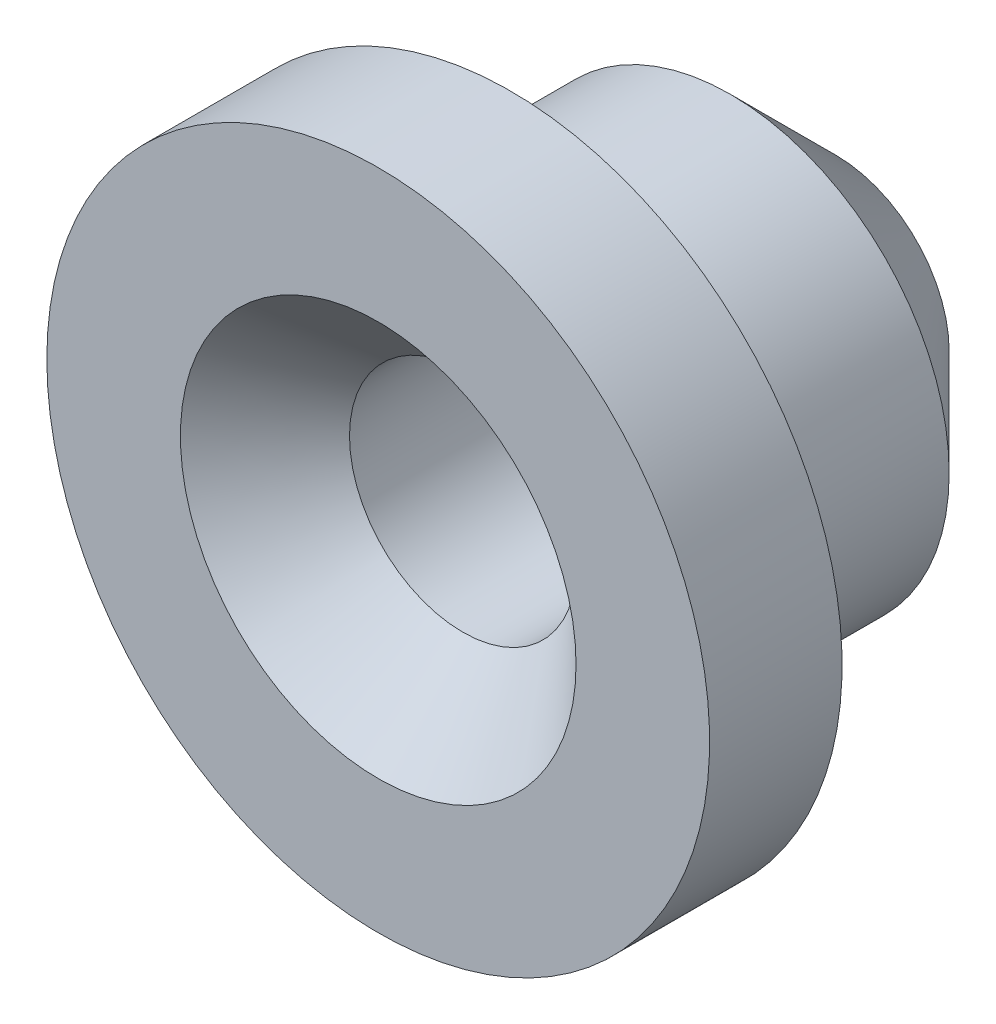
SolidWorks part; units mm, degrees
ref_plane "Front Plane" through (0, 0, 0) normal (0, 0, 1) x (1, 0, 0)
ref_plane "Top Plane" through (0, 0, 0) normal (0, 1, 0) x (1, 0, 0)
ref_plane "Right Plane" through (0, 0, 0) normal (1, 0, 0) x (0, 0, -1)
sketch "Sketch1" plane through (0, 0, 0) normal (0, 0, 1) x (1, 0, 0)
  circle A0 centre (-11.194, 3.0859) radius 4.9276
  dimension "D1" = 9.8552
extrude "Boss-Extrude1" add sketch "Sketch1" along normal blind 7.9375
sketch "Sketch4" plane through (0, 0, 0) normal (0, 0, -1) x (-1, 0, 0)
  circle A0 centre (11.194, 3.0859) radius 4.9276 construction
  circle A1 centre (11.194, 3.0859) radius 4.9276
extrude "Boss-Extrude2" add sketch "Sketch4" along normal blind 3.175 draft 45
hole_wizard "1/4-20 Tapped Hole1" positions "Sketch2" profile "Sketch3" tap size "1/4-20" standard "ANSI Inch"
sketch "Sketch2" plane through (0, 0, 7.9375) normal (0, 0, 1) x (1, 0, 0)
  point P0 (-11.194, 3.0859)
sketch "Sketch3" plane through (-11.194, 3.0859, 7.9375) normal (1, 0, 0) x (0, -1, 0)
  line L0 (0, 0) -> (0, 18.0438)
  line L1 (0, 18.0438) -> (2.5527, 16.51)
  line L2 (2.5527, 16.51) -> (2.5527, 1.905)
  line L3 (2.5527, 1.905) -> (4.4577, 0)
  line L5 (4.4577, 0) -> (0, 0)
  line L6 (-2.5527, 1.905) -> (-4.4577, 0) construction
  line L10 (0, 18.0438) -> (-2.5527, 16.51) construction
  line L11 (0, -6.35) -> (0, 107.95) construction
  dimension "Tap Drill Dia." = 5.1054
  dimension "Tap Drill Depth" = 16.51
  dimension "Near C'Sink Dia." = 8.9154
  dimension "Near C'Sink Angle" = 90
  dimension "Drill Angle" = 118
cosmetic thread "Hole Thread1" parameters "D1"=7.9375, "D2"=6.35
ref_axis "Axis1" through (-11.194, 3.0859, -2.3749) along (0, 0, 1)
ref_plane "Plane1" through (0, 3.0859, 0) normal (0, 1, 0) x (1, 0, 0)
sketch "Sketch5" plane through (0, 3.0859, 0) normal (0, 1, 0) x (1, 0, 0)
  line L0 (-16.1216, -4.953) -> (-18.6616, -4.953)
  line L1 (-18.6616, -4.953) -> (-18.6616, -7.9375)
  line L2 (-18.6616, -7.9375) -> (-16.1216, -7.9375)
  line L3 (-16.1216, -7.9375) -> (-6.2664, -7.9375) construction
  line L4 (-16.1216, -4.953) -> (-16.1216, -7.9375)
  line L5 (-16.1216, 0) -> (-6.2664, 0) construction
  dimension "D1" = 2.54
  dimension "D2" = 4.953
revolve "Revolve1" add sketch "Sketch5" angle 360 about axis through (-11.194, 3.0859, -2.3749) along (0, 0, 1)
